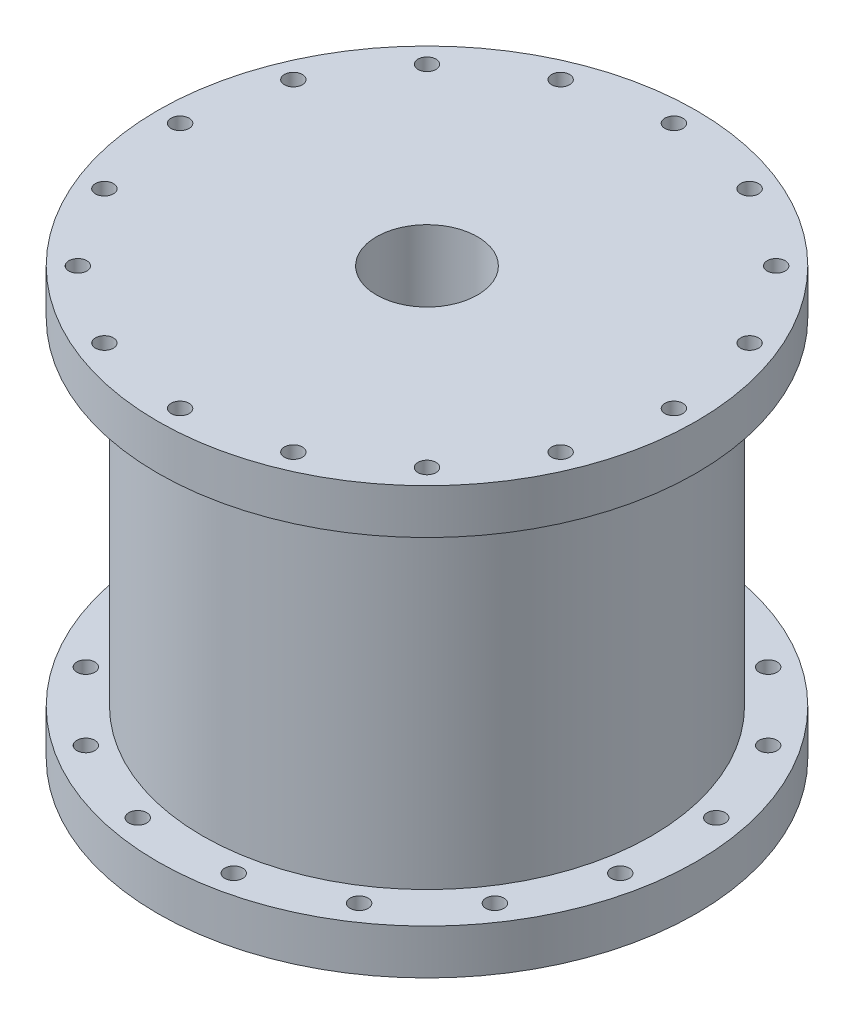
SolidWorks part; units mm, degrees
ref_plane "Front Plane" through (0, 0, 0) normal (0, 0, 1) x (1, 0, 0)
ref_plane "Top Plane" through (0, 0, 0) normal (0, 1, 0) x (1, 0, 0)
ref_plane "Right Plane" through (0, 0, 0) normal (1, 0, 0) x (0, 0, -1)
sketch "Sketch3" plane through (0, 0, 0) normal (1, 0, 0) x (0, 0, -1)
  line L0 (0, 0) -> (0, 47.4537)
  line L1 (0, 47.4537) -> (29.972, 47.4537)
  line L2 (29.972, 47.4537) -> (29.972, 42.4537)
  line L3 (29.972, 42.4537) -> (24.9933, 42.4537)
  line L4 (24.9933, 42.4537) -> (24.9933, 5)
  line L5 (24.9933, 5) -> (29.972, 5)
  line L6 (29.972, 5) -> (29.972, 0)
  line L7 (29.972, 0) -> (0, 0)
  line L8 (0, 0) -> (0.0836, -0.1672)
  line L9 (0, 47.4537) -> (0, 51.4239) construction
  dimension "D1" = 5
  dimension "Hub_Width" = 37.4537
  dimension "Hub Radius" = 29.972
revolve "Revolve1" add sketch "Sketch3" angle 360 about L9
sketch "Sketch4" plane through (0, 47.4537, 0) normal (0, 1, 0) x (1, 0, 0)
  circle A0 centre (0, 0) radius 5.6215
extrude "Cut-Extrude1" cut sketch "Sketch4" against normal through all
sketch "Sketch5" plane through (0, 42.4537, 0) normal (0, -1, 0) x (1, 0, 0)
  line L0 (0, 0) -> (0, 27.4827) construction
  line L1 (-8.2189, 28.8231) -> (-7.5363, 26.4292) construction
  line L2 (-7.5363, 26.4292) -> (-6.8536, 24.0352) construction
  circle A0 centre (0, 27.4827) radius 1
  circle A1 centre (0, 0) radius 24.9933 construction
  circle A2 centre (0, 0) radius 27.4827 construction
  circle A3 centre (0, 0) radius 29.972 construction
  dimension "D1" = 2
extrude "Cut-Extrude2" cut sketch "Sketch5" against normal through all
pattern_circular "CirPattern2" count 16 over 360 about axis through (0, 0, 0) along (0, 1, 0) of "Cut-Extrude2"
sketch "Sketch7" plane through (0, 0, 0) normal (0, -1, 0) x (1, 0, 0)
  line L0 (0, 0) -> (-5.8472, 29.3961) construction
  line L1 (-10.5172, 25.3907) -> (-5.3411, 26.8515) construction
  line L2 (-5.3411, 26.8515) -> (0, 27.4827) construction
  circle A0 centre (0, 0) radius 29.972 construction
  circle A1 centre (0, 0) radius 29.972 construction
  circle A2 centre (-5.3411, 26.8515) radius 1
  circle A3 centre (-10.5172, 25.3907) radius 1 construction
  circle A4 centre (0, 27.4827) radius 1 construction
  circle A5 centre (-10.5172, 25.3907) radius 1 construction
  circle A6 centre (0, 27.4827) radius 1 construction
  circle A7 centre (0, 0) radius 27.4827 construction
  dimension "D1" = 2
extrude "Cut-Extrude3" cut sketch "Sketch7" against normal up to next
pattern_circular "CirPattern3" count 16 over 360 about axis through (0, 0, 0) along (0, 1, 0) of "Cut-Extrude3"
equation "\"Spoke hole diameter\"= \"D1@Sketch5\""
